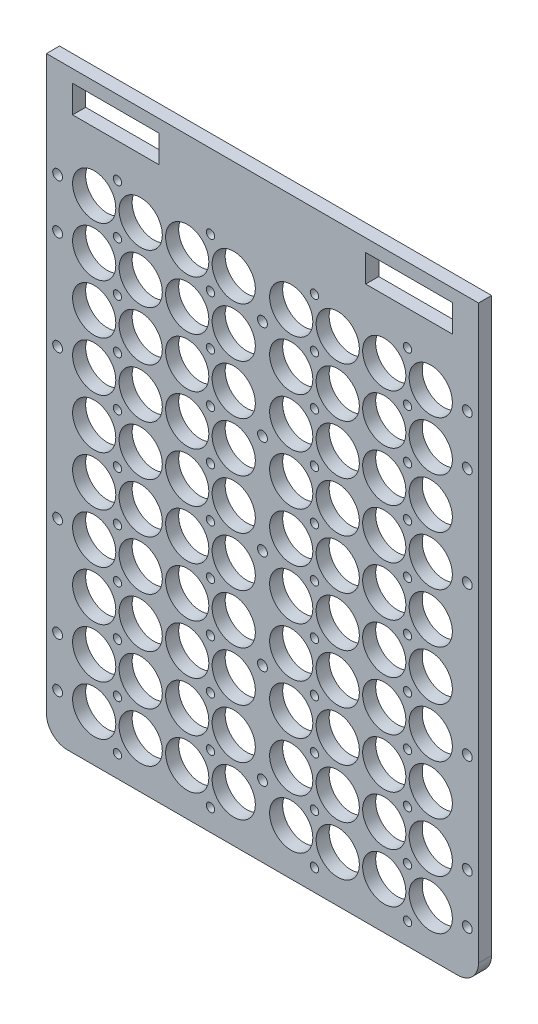
SolidWorks part; units mm, degrees
material "ABS"
ref_plane "X-Y Datum" through (0, 0, 0) normal (0, 0, 1) x (1, 0, 0)
ref_plane "X-Z Datum" through (0, 0, 0) normal (0, 1, 0) x (1, 0, 0)
ref_plane "Y-Z Datum" through (0, 0, 0) normal (1, 0, 0) x (0, 0, -1)
sketch "Sketch1" plane through (0, 0, 0) normal (0, 0, 1) x (1, 0, 0)
  line L0 (0, 10.5) -> (0, 13.63) construction
  line L1 (0, 12.065) -> (-11.77, 12.065) construction
  line L2 (78.318, 0) -> (85.258, 0) construction
  line L3 (10.5, 120.65) -> (12.106, 120.65) construction
  line L4 (0, 110.15) -> (0, 107.02) construction
  line L5 (-10.5, 0) -> (-17.77, 0) construction
  line L6 (-17.77, 0) -> (-17.77, 24.13) construction
  line L7 (81.788, 0) -> (81.788, 240.2038) construction
  line L8 (10.5, 24.13) -> (12.106, 24.13) construction
  line L9 (55.712, 24.13) -> (57.318, 24.13) construction
  line L10 (0, 4.7) -> (0, 19.43) construction
  line L11 (0, -4.7) -> (0, -22.605) construction
  line L12 (-10.5, 0) -> (-23.2, 0) construction
  line L13 (174.076, 217.17) -> (186.776, 217.17) construction
  line L14 (163.576, 227.67) -> (163.576, 244.18) construction
  line L16 (-23.2, -22.605) -> (186.776, -22.605)
  line L17 (-23.2, -22.605) -> (-23.2, 244.18)
  line L18 (-23.2, 244.18) -> (186.776, 244.18)
  line L19 (186.776, -22.605) -> (186.776, 244.18)
  circle A0 centre (0, 0) radius 10.5
  circle A1 centre (22.606, 0) radius 10.5
  circle A2 centre (45.212, 0) radius 10.5
  circle A3 centre (67.818, 0) radius 10.5
  circle A8 centre (22.606, 24.13) radius 10.5
  circle A9 centre (45.212, 24.13) radius 10.5
  circle A10 centre (67.818, 24.13) radius 10.5
  circle A15 centre (22.606, 48.26) radius 10.5
  circle A16 centre (45.212, 48.26) radius 10.5
  circle A17 centre (67.818, 48.26) radius 10.5
  circle A22 centre (22.606, 72.39) radius 10.5
  circle A23 centre (45.212, 72.39) radius 10.5
  circle A24 centre (67.818, 72.39) radius 10.5
  circle A29 centre (22.606, 96.52) radius 10.5
  circle A30 centre (45.212, 96.52) radius 10.5
  circle A31 centre (67.818, 96.52) radius 10.5
  circle A36 centre (22.606, 120.65) radius 10.5
  circle A37 centre (45.212, 120.65) radius 10.5
  circle A38 centre (67.818, 120.65) radius 10.5
  circle A43 centre (22.606, 144.78) radius 10.5
  circle A44 centre (45.212, 144.78) radius 10.5
  circle A45 centre (67.818, 144.78) radius 10.5
  circle A50 centre (22.606, 168.91) radius 10.5
  circle A51 centre (45.212, 168.91) radius 10.5
  circle A52 centre (67.818, 168.91) radius 10.5
  circle A57 centre (22.606, 193.04) radius 10.5
  circle A58 centre (45.212, 193.04) radius 10.5
  circle A59 centre (67.818, 193.04) radius 10.5
  circle A64 centre (22.606, 217.17) radius 10.5
  circle A65 centre (45.212, 217.17) radius 10.5
  circle A66 centre (67.818, 217.17) radius 10.5
  circle A71 centre (0, 24.13) radius 10.5
  circle A72 centre (0, 48.26) radius 10.5
  circle A73 centre (0, 72.39) radius 10.5
  circle A74 centre (0, 96.52) radius 10.5
  circle A75 centre (0, 120.65) radius 10.5
  circle A76 centre (0, 144.78) radius 10.5
  circle A77 centre (0, 168.91) radius 10.5
  circle A78 centre (0, 193.04) radius 10.5
  circle A79 centre (0, 217.17) radius 10.5
  circle A80 centre (95.758, 0) radius 10.5
  circle A81 centre (118.364, 0) radius 10.5
  circle A82 centre (140.97, 0) radius 10.5
  circle A83 centre (163.576, 0) radius 10.5
  circle A84 centre (118.364, 24.13) radius 10.5
  circle A85 centre (140.97, 24.13) radius 10.5
  circle A86 centre (163.576, 24.13) radius 10.5
  circle A87 centre (118.364, 48.26) radius 10.5
  circle A88 centre (140.97, 48.26) radius 10.5
  circle A89 centre (163.576, 48.26) radius 10.5
  circle A90 centre (118.364, 72.39) radius 10.5
  circle A91 centre (140.97, 72.39) radius 10.5
  circle A92 centre (163.576, 72.39) radius 10.5
  circle A93 centre (118.364, 96.52) radius 10.5
  circle A94 centre (140.97, 96.52) radius 10.5
  circle A95 centre (163.576, 96.52) radius 10.5
  circle A96 centre (118.364, 120.65) radius 10.5
  circle A97 centre (140.97, 120.65) radius 10.5
  circle A98 centre (163.576, 120.65) radius 10.5
  circle A99 centre (118.364, 144.78) radius 10.5
  circle A100 centre (140.97, 144.78) radius 10.5
  circle A101 centre (163.576, 144.78) radius 10.5
  circle A102 centre (118.364, 168.91) radius 10.5
  circle A103 centre (140.97, 168.91) radius 10.5
  circle A104 centre (163.576, 168.91) radius 10.5
  circle A105 centre (118.364, 193.04) radius 10.5
  circle A106 centre (140.97, 193.04) radius 10.5
  circle A107 centre (163.576, 193.04) radius 10.5
  circle A108 centre (118.364, 217.17) radius 10.5
  circle A109 centre (140.97, 217.17) radius 10.5
  circle A110 centre (163.576, 217.17) radius 10.5
  circle A111 centre (95.758, 24.13) radius 10.5
  circle A112 centre (95.758, 48.26) radius 10.5
  circle A113 centre (95.758, 72.39) radius 10.5
  circle A114 centre (95.758, 96.52) radius 10.5
  circle A115 centre (95.758, 120.65) radius 10.5
  circle A116 centre (95.758, 144.78) radius 10.5
  circle A117 centre (95.758, 168.91) radius 10.5
  circle A118 centre (95.758, 193.04) radius 10.5
  circle A119 centre (95.758, 217.17) radius 10.5
  circle A120 centre (-17.77, 0) radius 1.5274
  circle A121 centre (-17.77, 24.13) radius 1.5274
  circle A122 centre (-17.77, 48.26) radius 1.5274 [skipped]
  circle A123 centre (-17.77, 72.39) radius 1.5274
  circle A124 centre (-17.77, 96.52) radius 1.5274 [skipped]
  circle A125 centre (-17.77, 120.65) radius 1.5274 [skipped]
  circle A126 centre (-17.77, 144.78) radius 1.5274
  circle A127 centre (-17.77, 168.91) radius 1.5274 [skipped]
  circle A128 centre (-17.77, 193.04) radius 1.5274
  circle A129 centre (-17.77, 217.17) radius 1.5274
  circle A130 centre (181.346, 144.78) radius 1.5274
  circle A131 centre (181.346, 72.39) radius 1.5274
  circle A132 centre (181.346, 0) radius 1.5274
  circle A133 centre (181.346, 217.17) radius 1.5274
  circle A134 centre (11.303, 12.065) radius 2.032
  circle A135 centre (56.515, 12.065) radius 2.032
  circle A136 centre (56.515, 36.195) radius 2.032
  circle A137 centre (56.515, 60.325) radius 2.032
  circle A138 centre (56.515, 84.455) radius 2.032
  circle A139 centre (56.515, 108.585) radius 2.032
  circle A140 centre (56.515, 132.715) radius 2.032
  circle A141 centre (56.515, 156.845) radius 2.032
  circle A142 centre (56.515, 180.975) radius 2.032
  circle A143 centre (56.515, 205.105) radius 2.032
  circle A144 centre (56.515, 229.235) radius 2.032
  circle A145 centre (11.303, 36.195) radius 2.032
  circle A146 centre (11.303, 60.325) radius 2.032
  circle A147 centre (11.303, 84.455) radius 2.032
  circle A148 centre (11.303, 108.585) radius 2.032
  circle A149 centre (11.303, 132.715) radius 2.032
  circle A150 centre (11.303, 156.845) radius 2.032
  circle A151 centre (11.303, 180.975) radius 2.032
  circle A152 centre (11.303, 205.105) radius 2.032
  circle A153 centre (11.303, 229.235) radius 2.032
  circle A154 centre (56.515, -12.065) radius 2.032
  circle A155 centre (11.303, -12.065) radius 2.032
  circle A156 centre (107.061, 229.235) radius 2.032
  circle A157 centre (152.273, 229.235) radius 2.032
  circle A158 centre (152.273, 205.105) radius 2.032
  circle A159 centre (107.061, 205.105) radius 2.032
  circle A160 centre (107.061, 180.975) radius 2.032
  circle A161 centre (152.273, 180.975) radius 2.032
  circle A162 centre (152.273, 156.845) radius 2.032
  circle A163 centre (107.061, 156.845) radius 2.032
  circle A164 centre (107.061, 132.715) radius 2.032
  circle A165 centre (152.273, 132.715) radius 2.032
  circle A166 centre (152.273, 108.585) radius 2.032
  circle A167 centre (107.061, 108.585) radius 2.032
  circle A168 centre (107.061, 84.455) radius 2.032
  circle A169 centre (152.273, 84.455) radius 2.032
  circle A170 centre (152.273, 60.325) radius 2.032
  circle A171 centre (107.061, 60.325) radius 2.032
  circle A172 centre (107.061, 36.195) radius 2.032
  circle A173 centre (152.273, 36.195) radius 2.032
  circle A174 centre (152.273, 12.065) radius 2.032
  circle A175 centre (107.061, 12.065) radius 2.032
  circle A176 centre (107.061, -12.065) radius 2.032
  circle A177 centre (152.273, -12.065) radius 2.032
  circle A178 centre (0, 0) radius 4.7 construction
  circle A179 centre (0, 24.13) radius 4.7 construction
  circle A180 centre (-17.77, 0) radius 6.35 construction
  circle A181 centre (181.346, 24.13) radius 1.5274
  circle A182 centre (181.346, 193.04) radius 1.5274
  circle A185 centre (81.788, 12.065) radius 1.4304
  circle A186 centre (81.788, 36.195) radius 1.4304 [skipped]
  circle A187 centre (81.788, 60.325) radius 1.4304
  circle A188 centre (81.788, 84.455) radius 1.4304 [skipped]
  circle A189 centre (81.788, 108.585) radius 1.4304
  circle A190 centre (81.788, 132.715) radius 1.4304 [skipped]
  circle A191 centre (81.788, 156.845) radius 1.4304
  circle A192 centre (81.788, 180.975) radius 1.4304 [skipped]
  circle A193 centre (81.788, 205.105) radius 1.4304
  circle A194 centre (81.788, 229.235) radius 1.4304 [skipped]
  dimension "D1" = 4
  dimension "D6" = 21
  dimension "D10" = 2
  dimension "D13" = 10
  dimension "D3" = 11.77
  dimension "D4" = 4
  dimension "D7" = 7.27
  dimension "D9" = 27.94
  dimension "D2" = 10
  dimension "D5" = 10
  dimension "D8" = 10
  dimension "D11" = 10
  dimension "D12" = 2
extrude "Boss-Extrude1" add sketch "Sketch1" along normal blind 6.35
hole_wizard "M4 Clearance Hole1" positions "Sketch2" profile "Sketch3" hole size "M4" standard "ANSI Metric" end condition through all
sketch "Sketch2" plane through (0, 0, 6.35) normal (0, 0, 1) x (1, 0, 0)
  point P0 (-17.77, 217.17)
  point P3 (-17.77, 144.78)
  point P6 (-17.77, 72.39)
  point P9 (-17.77, 0)
  point P12 (181.346, 0)
  point P15 (181.346, 72.39)
  point P18 (181.346, 144.78)
  point P21 (181.346, 217.17)
  point P25 (181.346, 24.13)
  point P28 (-17.77, 24.13)
  point P31 (-17.77, 193.04)
  point P34 (181.346, 193.04)
  point P38 (81.788, 12.065)
  point P41 (81.788, 60.325)
  point P44 (81.788, 108.585)
  point P56 (81.788, 156.845)
  point P59 (81.788, 205.105)
sketch "Sketch3" plane through (-17.77, 217.17, 6.35) normal (1, 0, 0) x (0, -1, 0)
  line L0 (0, 0) -> (0, 6.35)
  line L1 (0, 6.35) -> (2.4, 6.35)
  line L2 (2.4, 6.35) -> (2.4, 0)
  line L5 (2.4, 0) -> (0, 0)
  line L11 (0, -6.35) -> (0, 107.95) construction
  dimension "Thru Hole Dia." = 4.8
  dimension "Thru Hole Depth" = 6.35
fillet "Fillet1" radius 10.16 2 edges at (186.776, -22.605, 3.175) (-23.2, -22.605, 3.175)
sketch "Sketch5" plane through (0, 0, 6.35) normal (0, 0, 1) x (1, 0, 0)
  line L0 (0, 4.7) -> (-10.5, 4.7) construction
  line L1 (-10.5, 0) -> (-10.5, 4.7) construction
  line L2 (78.318, 24.13) -> (78.318, 15.2474) construction
  line L3 (0, 19.43) -> (78.318, 19.43) construction
  line L4 (0, -4.7) -> (-10.5, -4.7) construction
  line L5 (-10.5, 4.7) -> (78.318, 4.7)
  line L6 (-10.5, 4.7) -> (-10.5, 19.43)
  line L7 (-10.5, 19.43) -> (78.318, 19.43)
  line L8 (78.318, 4.7) -> (78.318, 19.43)
  line L9 (-10.5, -4.7) -> (174.076, -4.7)
  line L10 (-10.5, -4.7) -> (-10.5, -19.43)
  line L11 (-10.5, -19.43) -> (174.076, -19.43)
  line L12 (174.076, -4.7) -> (174.076, -19.43)
  circle A0 centre (0, 0) radius 4.7
  circle A1 centre (0, 24.13) radius 4.7
  circle A2 centre (11.303, -12.065) radius 2.032
  circle A3 centre (56.515, -12.065) radius 2.032
  circle A4 centre (0, 0) radius 10.5 construction
  circle A5 centre (67.818, 24.13) radius 10.5 construction
  circle A6 centre (11.303, 12.065) radius 2.032
  circle A7 centre (56.515, 12.065) radius 2.032
  circle A8 centre (107.061, -12.065) radius 2.032
  circle A9 centre (152.273, -12.065) radius 2.032
sketch "Sketch6" plane through (0, 0, 6.35) normal (0, 0, 1) x (1, 0, 0)
  line L0 (-23.2, 244.18) -> (-23.2, 265.3865)
  line L1 (-23.2, 265.3865) -> (186.776, 265.3865)
  line L2 (186.776, 265.3865) -> (186.776, 244.18)
  line L3 (186.776, 244.18) -> (174.076, 244.18)
  line L4 (81.788, 265.3865) -> (81.788, 235.5201) construction
  line L6 (-10.5, 245.9386) -> (-10.5, 259.2276)
  line L7 (-10.5, 259.2276) -> (31.6205, 259.2276)
  line L8 (31.6205, 245.9386) -> (31.6205, 259.2276)
  line L9 (174.076, 259.2276) -> (131.9555, 259.2276)
  line L10 (131.9555, 245.9386) -> (131.9555, 259.2276)
  line L12 (174.076, 245.9386) -> (174.076, 259.2276)
  line L13 (-10.5, 244.18) -> (-23.2, 244.18)
  line L14 (107.8071, 244.18) -> (55.7689, 244.18)
  line L15 (131.9555, 245.9386) -> (174.076, 245.9386)
  line L17 (-10.5, 245.9386) -> (31.6205, 245.9386)
  line L18 (-10.5, 244.18) -> (55.7689, 244.18)
  line L19 (107.8071, 244.18) -> (174.076, 244.18)
extrude "Boss-Extrude2" add sketch "Sketch6" against normal through all
